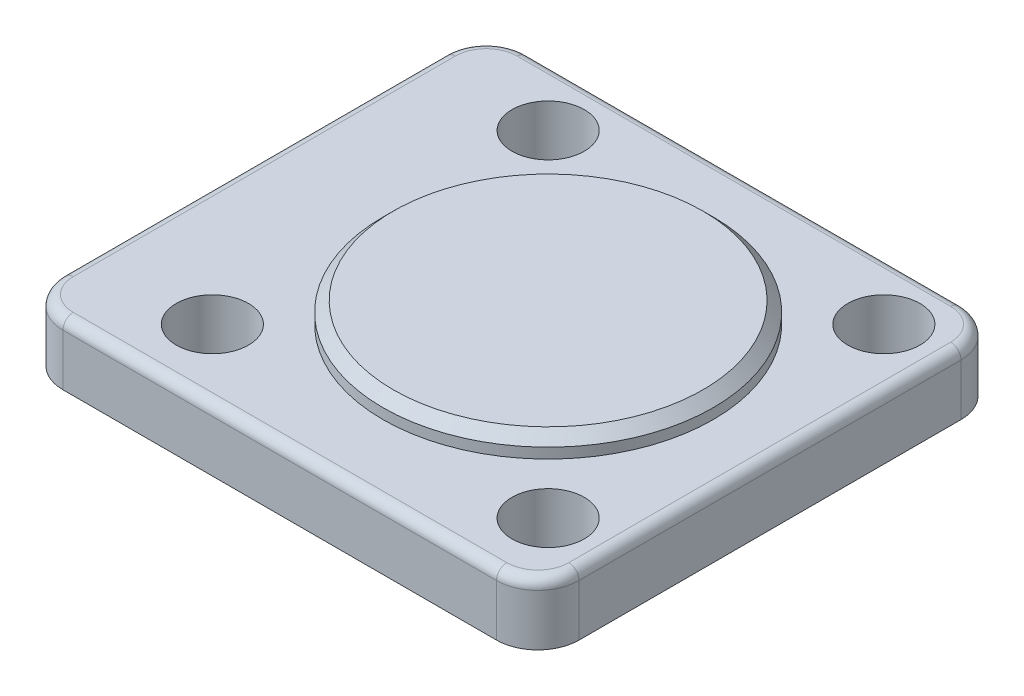
SolidWorks part; units mm, degrees
ref_plane "Front Plane" through (0, 0, 0) normal (0, 0, 1) x (1, 0, 0)
ref_plane "Top Plane" through (0, 0, 0) normal (0, 1, 0) x (1, 0, 0)
ref_plane "Right Plane" through (0, 0, 0) normal (1, 0, 0) x (0, 0, -1)
sketch "Sketch1" plane through (0, 0, 0) normal (0, 1, 0) x (1, 0, 0)
  line L1 (-24, 22) -> (18, 22)
  line L2 (-28, 18) -> (-28, -19)
  line L3 (-24, -23) -> (18, -23)
  line L4 (22, 18) -> (22, -19)
  arc A0 (18, 22) -> (22, 18) centre (18, 18) cw
  arc A1 (18, -23) -> (22, -19) centre (18, -19) ccw
  arc A2 (-28, -19) -> (-24, -23) centre (-24, -19) ccw
  arc A3 (-24, 22) -> (-28, 18) centre (-24, 18) ccw
  point P0 (0, 0)
  point P8 (22, 22)
  point P13 (-28, -23)
  point P16 (-28, 22)
  dimension "D5" = 4
  dimension "D1" = 50
  dimension "D2" = 45
  dimension "D3" = 22
  dimension "D4" = 22
extrude "Boss-Extrude1" add sketch "Sketch1" along normal blind 6
sketch "Sketch2" plane through (0, 6, 0) normal (0, 1, 0) x (1, 0, 0)
  line L0 (16.2635, 16.2635) -> (0, 0) construction
  line L1 (0, 0) -> (15.544, 0) construction
  circle A0 centre (0, 0) radius 23 construction
  circle A1 centre (16.2635, 16.2635) radius 3.5
  circle A2 centre (16.2635, -16.2635) radius 3.5
  circle A3 centre (-16.2635, -16.2635) radius 3.5
  circle A4 centre (-16.2635, 16.2635) radius 3.5
  point P16 (0, 0)
  dimension "D1" = 46
  dimension "D2" = 7
  dimension "D3" = 45
  dimension "D4" = 4
extrude "Cut-Extrude1" cut sketch "Sketch2" against normal through all
sketch "Sketch3" plane through (0, 6, 0) normal (0, 1, 0) x (1, 0, 0)
  circle A0 centre (0, 0) radius 16
  point P3 (0, 0)
  dimension "D1" = 32
extrude "Boss-Extrude2" add sketch "Sketch3" along normal blind 2
chamfer "Chamfer1" distance 1 angle 45 1 edges at (0, 8, 16)
fillet "Fillet1" radius 1 8 edges at (-26.8284, 6, -20.8284) (-3, 6, -22) (20.8284, 6, -20.8284) (22, 6, 0.5) (20.8284, 6, 21.8284) (-3, 6, 23) (-26.8284, 6, 21.8284) (-28, 6, 0.5)
